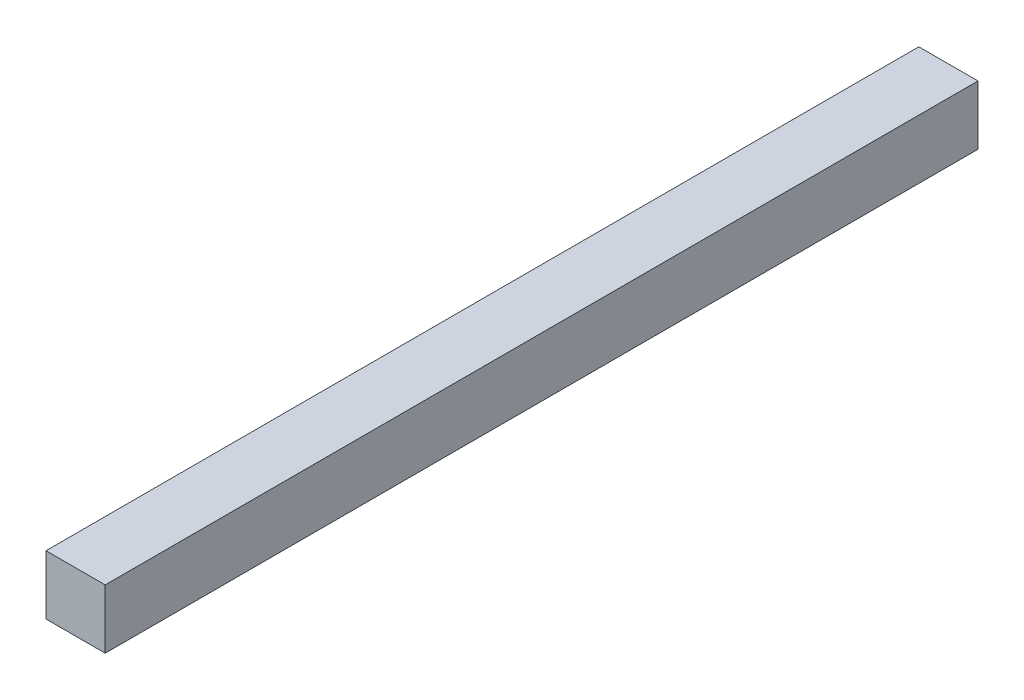
SolidWorks part; units mm, degrees
ref_plane "Plan de face" through (0, 0, 0) normal (0, 0, 1) x (1, 0, 0)
ref_plane "Plan de dessus" through (0, 0, 0) normal (0, 1, 0) x (1, 0, 0)
ref_plane "Plan de droite" through (0, 0, 0) normal (1, 0, 0) x (0, 0, -1)
sketch "Esquisse1" plane through (0, 0, 0) normal (0, 0, 1) x (1, 0, 0)
  line L5 (-600, 0) -> (-600, -31.25)
  line L6 (-600, -31.25) -> (-215, -125)
  line L7 (-215, -125) -> (0, -125)
  line L8 (0, -125) -> (0, 0)
  line L9 (0, 0) -> (-600, 0)
  line L10 (-600, 0) -> (-600, -31.25)
  line L11 (-600, -31.25) -> (-215, -125)
  line L12 (-215, -125) -> (0, -125)
  line L13 (0, -125) -> (0, 0)
  line L18 (-157.5, 0) -> (-600, 0)
  line L23 (-40, -10) -> (-50, -10)
  line L24 (-50, 0) -> (-50, -10)
  line L25 (-40, -10) -> (-40, 0)
  line L27 (-40, 0) -> (-50, 0)
  line L28 (0, 0) -> (-600, 0) construction
  dimension "D2" = 10
  dimension "D3" = 10
  dimension "D4" = 40
  dimension "D1" = 0
extrude "Boss.-Extru.1" add sketch "Esquisse1" along normal up to vertex (170 mm away)
